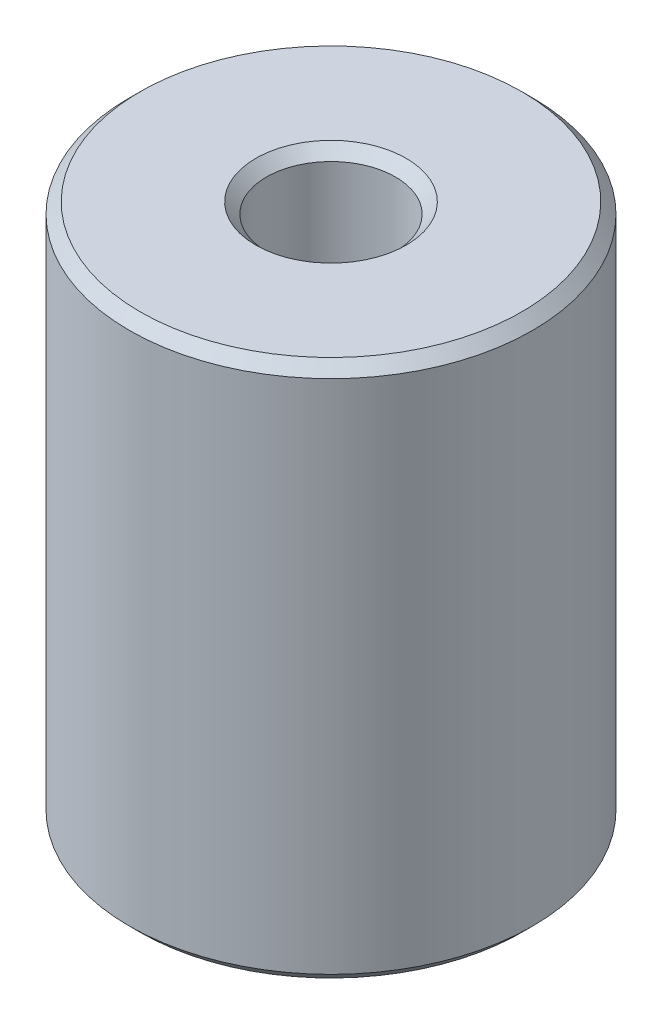
SolidWorks part; units mm, degrees
ref_plane "Front Plane" through (0, 0, 0) normal (0, 0, 1) x (1, 0, 0)
ref_plane "Top Plane" through (0, 0, 0) normal (0, 1, 0) x (1, 0, 0)
ref_plane "Right Plane" through (0, 0, 0) normal (1, 0, 0) x (0, 0, -1)
sketch "Sketch1" plane through (0, 0, 0) normal (0, 1, 0) x (1, 0, 0)
  circle A0 centre (0, 0) radius 1.524
  circle A1 centre (0, 0) radius 4.7625
  dimension "D1" = 9.525
  dimension "D2" = 3.048
extrude "Boss-Extrude1" add sketch "Sketch1" along normal blind 12.7
chamfer "Chamfer1" distance 0.254 angle 45 4 edges at (0, 12.7, 1.524) (0, 12.7, 4.7625) (0, 0, 1.524) (0, 0, 4.7625)
ref_plane "Plane1" through (-4.7625, 0, 0) normal (-1, 0, 0) x (0, 0, 1)
hole_wizard "#6-32 Tapped Hole1" [suppressed] positions "Sketch2" profile "Sketch3" tap size "#6-32" standard "ANSI Inch"
sketch "Sketch2" plane through (-4.7625, 0, 0) normal (-1, 0, 0) x (0, 0, 1)
  point P0 (0, 6.4679)
cosmetic thread "Hole Thread1" [suppressed] parameters "D2"=3.5052
sketch "Sketch3" plane through (-4.7625, 6.4679, 0) normal (0, 1, 0) x (0, 0, 1)
  line L0 (0, 0) -> (0, 5.1307)
  line L1 (0, 5.1307) -> (1.3525, 4.318)
  line L2 (1.3525, 4.318) -> (1.3525, 0)
  line L5 (1.3525, 0) -> (0, 0)
  line L10 (0, 5.1307) -> (-1.3526, 4.318) construction
  line L11 (0, -6.35) -> (0, 107.95) construction
  dimension "Tap Drill Dia." = 2.7051
  dimension "Tap Drill Depth" = 4.318
  dimension "Drill Angle" = 118
